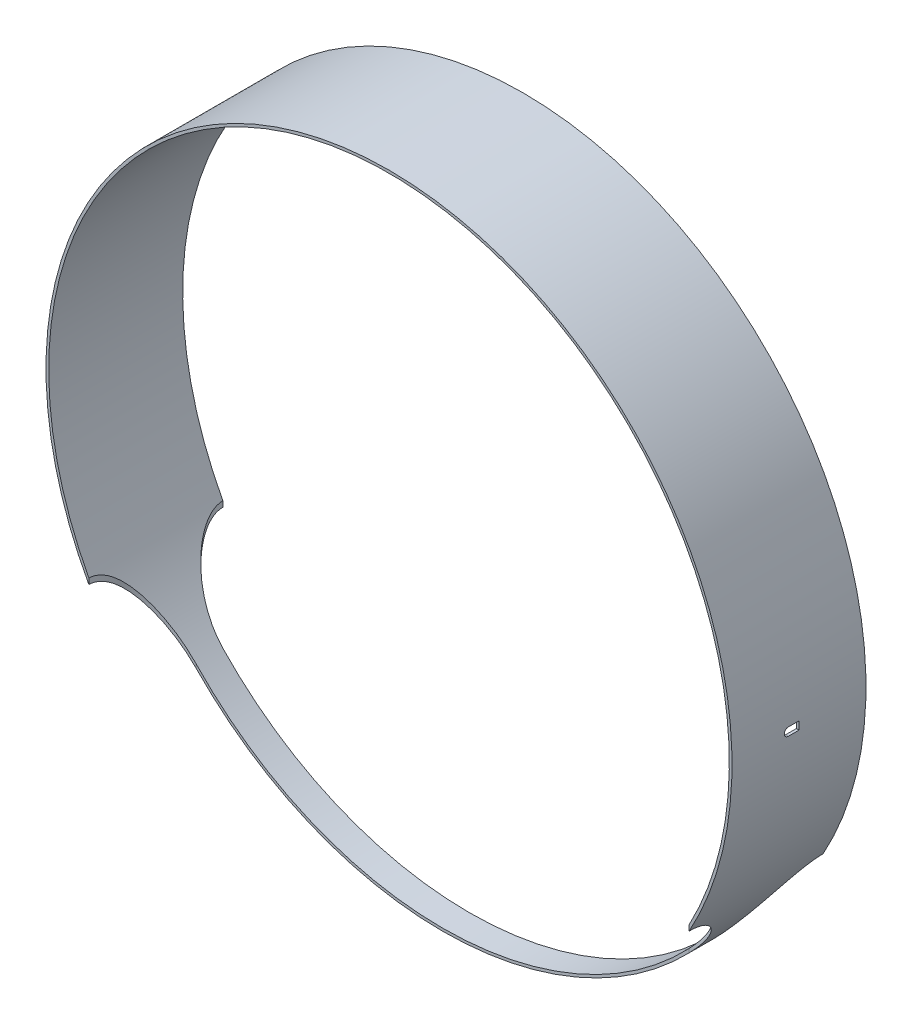
SolidWorks part; units mm, degrees
ref_plane "前视基准面" through (0, 0, 0) normal (0, 0, 1) x (1, 0, 0)
ref_plane "上视基准面" through (0, 0, 0) normal (0, 1, 0) x (1, 0, 0)
ref_plane "右视基准面" through (0, 0, 0) normal (1, 0, 0) x (0, 0, -1)
sketch "草图3" plane through (0, 0, 0) normal (0, 0, 1) x (1, 0, 0)
  circle A0 centre (0, 0) radius 64
  circle A1 centre (0, 0) radius 63.5
  dimension "D1" = 128
  dimension "D2" = 127
extrude "凸台-拉伸2" add sketch "草图3" along normal blind 25
sketch "草图4" plane through (0, 0, 0) normal (0, 1, 0) x (1, 0, 0)
  line L1 (63.5, 0) -> (-63.5, 0) construction
  line L3 (64, 0) -> (-64, 0) construction
  line L5 (-46, -10) -> (46, -10)
  line L7 (0, -55) -> (0, 55) construction
  line L10 (-56, 0) -> (56, 0)
  line L11 (-64, -12.5) -> (64, -12.5) construction
  line L12 (-64, 0) -> (-64, -25) construction
  line L13 (64, -25) -> (64, 0) construction
  line L14 (-46, -15) -> (46, -15)
  line L15 (-56, -25) -> (56, -25)
  arc A0 (-56, 0) -> (-46, -10) centre (-46, 0) ccw
  arc A2 (56, 0) -> (46, -10) centre (46, 0) cw
  arc A3 (-56, -25) -> (-46, -15) centre (-46, -25) cw
  arc A4 (56, -25) -> (46, -15) centre (46, -25) ccw
  dimension "D6" = 10
extrude "切除-拉伸2" cut sketch "草图4" against normal blind 200
sketch "草图6" plane through (0, 0, 0) normal (1, 0, 0) x (0, 0, -1)
  line L2 (-12.5, -0.75) -> (-12.5, 0.75)
  line L4 (-25, 64) -> (-25, -30.9839) construction
  line L5 (-12.5, 0.75) -> (-12.5, 2.648) construction
  line L6 (-14.5, 0.75) -> (-12.5, 0.75)
  line L7 (-14.5, -0.75) -> (-12.5, -0.75)
  arc A1 (-14.5, 0.75) -> (-14.5, -0.75) centre (-14.5, 0) ccw
  dimension "D4" = 12.5
extrude "切除-拉伸3" cut sketch "草图6" along normal blind 200
